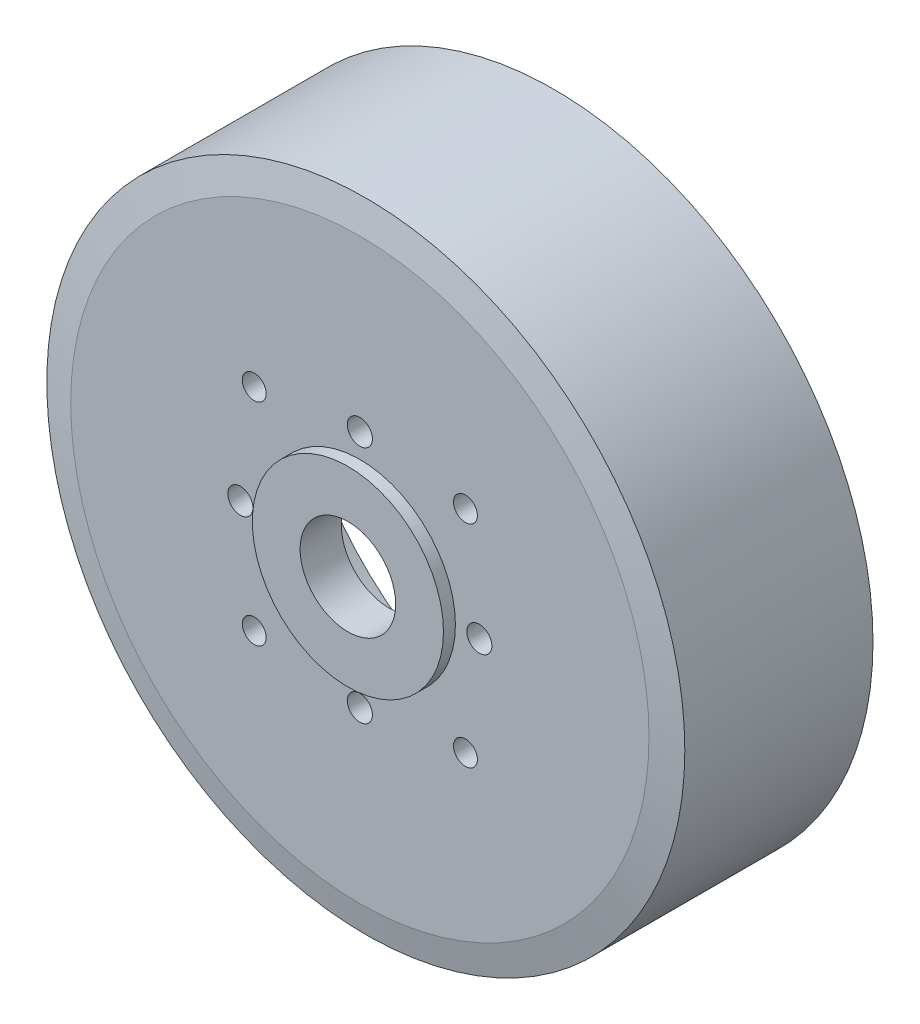
SolidWorks part; units mm, degrees
ref_plane "Front Plane" through (0, 0, 0) normal (0, 0, 1) x (1, 0, 0)
ref_plane "Top Plane" through (0, 0, 0) normal (0, 1, 0) x (1, 0, 0)
ref_plane "Right Plane" through (0, 0, 0) normal (1, 0, 0) x (0, 0, -1)
sketch "Sketch3" plane through (0, 0, 0) normal (0, 0, 1) x (1, 0, 0)
  circle A0 centre (0, 0) radius 53.4
  dimension "D1" = 106.8
extrude "Boss-Extrude1" add sketch "Sketch3" against normal blind 38.5
sketch "Sketch4" plane through (0, 0, 0) normal (0, 0, 1) x (1, 0, 0)
  circle A0 centre (0, 0) radius 8
  dimension "D1" = 16
extrude "Cut-Extrude1" cut sketch "Sketch4" against normal through all
sketch "Sketch5" plane through (0, 0, 0) normal (0, 0, 1) x (1, 0, 0)
  line L0 (0, 0) -> (-17.6777, 17.6777) construction
  line L1 (0, 0) -> (0, 25) construction
  line L2 (0, 0) -> (17.6777, -17.6777) construction
  line L3 (0, 0) -> (17.6777, 17.6777) construction
  line L4 (0, 0) -> (-17.6777, -17.6777) construction
  arc A0 (-19.0342, -16.208) -> (-16.208, -19.0342) centre (0, 0) ccw
  circle A1 centre (-17.6777, 17.6777) radius 2
  circle A2 centre (17.6777, 17.6777) radius 2
  circle A3 centre (-17.6777, -17.6777) radius 2
  circle A4 centre (17.6777, -17.6777) radius 2
  dimension "D1" = 50
  dimension "D4" = 4
  dimension "D5" = 4
  dimension "D6" = 4
  dimension "D7" = 4
  dimension "D2" = 45
  dimension "D3" = 45
extrude "Cut-Extrude2" cut sketch "Sketch5" against normal blind 20 contours A4 | A2 | A1 | A3
sketch "Sketch6" plane through (0, 0, 0) normal (0, 0, 1) x (1, 0, 0)
  circle A0 centre (0, 0) radius 16
  circle A1 centre (0, 0) radius 8
  dimension "D1" = 32
  dimension "D2" = 16
extrude "Boss-Extrude3" add sketch "Sketch6" along normal blind 2
sketch "Sketch7" plane through (0, 0, 0) normal (0, 0, 1) x (1, 0, 0)
  line L0 (0, 0) -> (20, 0) construction
  line L1 (0, 0) -> (0, 20) construction
  arc A0 (-19.8898, 2.0971) -> (-19.8898, -2.0971) centre (0, 0) ccw
  circle A1 centre (0, 20) radius 2.1
  circle A2 centre (20, 0) radius 2.1
  circle A3 centre (-20, 0) radius 2.1
  circle A4 centre (0, -20) radius 2.1
  arc A5 (-2.0971, -19.8898) -> (2.0971, -19.8898) centre (0, 0) ccw
  arc A6 (19.8898, -2.0971) -> (19.8898, 2.0971) centre (0, 0) ccw
  arc A7 (2.0971, 19.8898) -> (-2.0971, 19.8898) centre (0, 0) ccw
  dimension "D1" = 40
  dimension "D2" = 4.2
  dimension "D3" = 4.2
  dimension "D4" = 4.2
  dimension "D5" = 4.2
extrude "Cut-Extrude3" cut sketch "Sketch7" against normal blind 20 contours A4 | A2 | A1 | A3
sketch "Sketch8" plane through (0, 0, -38.5) normal (0, 0, -1) x (-1, 0, 0)
  line L0 (0, 27.5) -> (0, 30) construction
  line L1 (0, 0) -> (0, -30) construction
  line L2 (27.5, 0) -> (30, 0) construction
  line L3 (0, 0) -> (-30, 0) construction
  arc A0 (-29.8958, 2.4978) -> (-29.8958, -2.4978) centre (0, 0) ccw
  circle A1 centre (0, 30) radius 2.5
  circle A2 centre (30, 0) radius 2.5
  circle A3 centre (0, -30) radius 2.5
  circle A4 centre (-30, 0) radius 2.5
  arc A5 (2.4978, 29.8958) -> (-2.4978, 29.8958) centre (0, 0) ccw
  arc A6 (29.8958, -2.4978) -> (29.8958, 2.4978) centre (0, 0) ccw
  arc A7 (-2.4978, -29.8958) -> (2.4978, -29.8958) centre (0, 0) ccw
  dimension "D1" = 60
  dimension "D2" = 5
  dimension "D3" = 5
  dimension "D4" = 5
  dimension "D5" = 5
extrude "Cut-Extrude4" cut sketch "Sketch8" against normal blind 20 contours A4 | A1 | A2 | A3
chamfer "Chamfer1" distance 1 distance2 5 1 edges at (53.4, 0, 0)
sketch "Sketch9" plane through (0, 0, -38.5) normal (0, 0, -1) x (-1, 0, 0)
  circle A0 centre (0, 0) radius 53.4 construction
  circle A1 centre (0, 0) radius 53.4
extrude "Cut-Extrude5" cut sketch "Sketch9" against normal blind 6 contours A1
sketch "Sketch10" plane through (0, 0, -32.5) normal (0, 0, -1) x (-1, 0, 0)
  circle A0 centre (0, 0) radius 44.75
  dimension "D1" = 89.5
extrude "Cut-Extrude6" cut sketch "Sketch10" against normal blind 27.6
